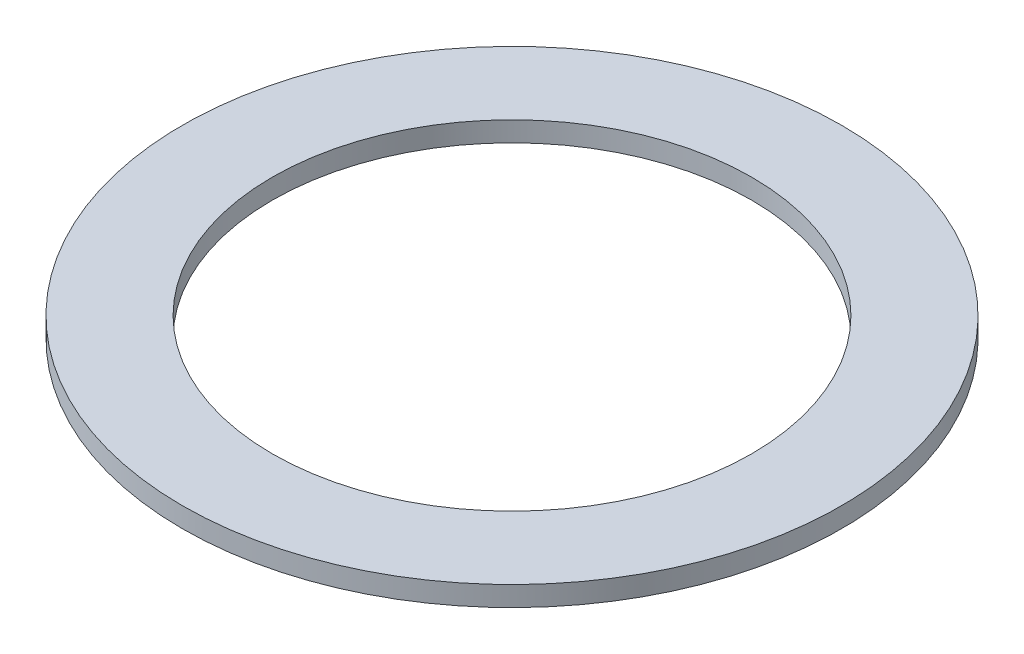
SolidWorks part; units mm, degrees
material "BUTYL"
ref_plane "Ön Düzlem" through (0, 0, 0) normal (0, 0, 1) x (1, 0, 0)
ref_plane "Üst Düzlem" through (0, 0, 0) normal (0, 1, 0) x (1, 0, 0)
ref_plane "Sağ Düzlem" through (0, 0, 0) normal (1, 0, 0) x (0, 0, -1)
sketch "Sketch2" plane through (0, 0, 0) normal (0, 1, 0) x (1, 0, 0)
  circle A0 centre (0, 0) radius 16.5
  circle A1 centre (0, 0) radius 12
  dimension "D1" = 24
  dimension "D2" = 33
extrude "Boss-Extrude1" add sketch "Sketch2" along normal blind 1
